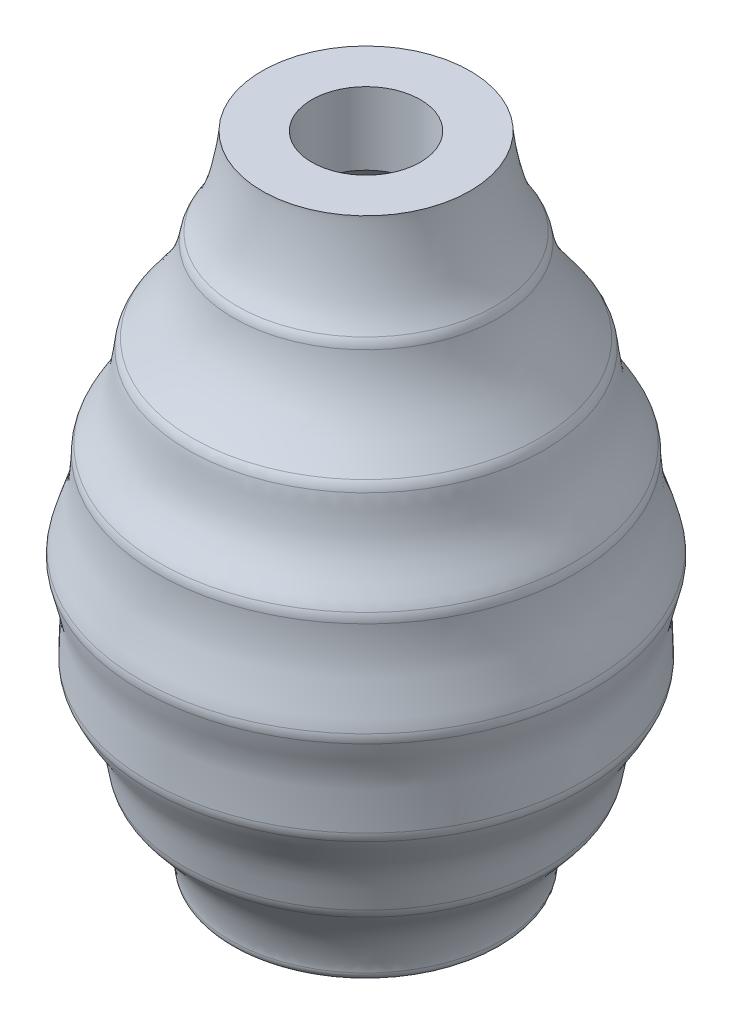
SolidWorks part; units mm, degrees
ref_plane "Front Plane" through (0, 0, 0) normal (0, 0, 1) x (1, 0, 0)
ref_plane "Top Plane" through (0, 0, 0) normal (0, 1, 0) x (1, 0, 0)
ref_plane "Right Plane" through (0, 0, 0) normal (1, 0, 0) x (0, 0, -1)
sketch "Sketch1" plane through (0, 0, 0) normal (0, 0, 1) x (1, 0, 0)
  line L0 (0, 0) -> (0, 16.1018)
  line L1 (0, 16.1018) -> (0, 32.2036)
  line L2 (0, 32.2036) -> (0, 48.3054)
  line L3 (0, 48.3054) -> (0, 64.4071)
  line L4 (0, 64.4071) -> (0, 80.5089)
  line L5 (0, 80.5089) -> (0, 96.6107)
  line L6 (0, 96.6107) -> (0, 112.7125)
  line L7 (0, 112.7125) -> (18.2562, 112.7125)
  line L8 (18.2562, 112.7125) -> (23.0187, 96.6107) construction
  line L9 (23.0187, 96.6107) -> (30.9563, 80.5089) construction
  line L10 (30.9563, 80.5089) -> (36.5125, 64.4071) construction
  line L11 (36.5125, 64.4071) -> (39.6875, 48.3054) construction
  line L12 (39.6875, 48.3054) -> (38.1, 32.2036) construction
  line L13 (38.1, 32.2036) -> (31.75, 16.1018) construction
  line L14 (31.75, 16.1018) -> (22.225, 0) construction
  line L15 (22.225, 0) -> (0, 0)
  line L16 (0, 96.6107) -> (23.0187, 96.6107) construction
  line L17 (0, 80.5089) -> (30.9563, 80.5089) construction
  line L18 (0, 64.4071) -> (36.5125, 64.4071) construction
  line L19 (0, 48.3054) -> (39.6875, 48.3054) construction
  line L20 (0, 32.2036) -> (38.1, 32.2036) construction
  line L21 (0, 16.1018) -> (31.75, 16.1018) construction
  line L22 (18.2562, 112.7125) -> (18.2563, 118.6616) construction
  line L23 (23.2087, 95.8487) -> (23.3634, 94.8513) construction
  arc A0 (22.6174, 97.3727) -> (23.2087, 95.8487) centre (19.4437, 95.2648) cw
  arc A1 (30.4914, 81.2709) -> (31.1875, 79.7469) centre (27.4587, 78.9647) cw
  arc A2 (36.2772, 65.1691) -> (36.5844, 63.6451) centre (32.7745, 63.6701) cw
  arc A3 (39.6062, 49.0674) -> (39.6149, 47.5434) centre (35.8776, 48.284) cw
  arc A4 (38.1686, 32.9656) -> (37.8684, 31.4416) centre (34.3588, 32.9243) cw
  arc A5 (31.972, 16.8638) -> (31.3316, 15.3398) centre (28.2229, 17.5426) cw
  arc A6 (23.749, 1.524) -> (22.225, 0) centre (22.225, 1.524) cw
  spline S0 degree 3 poles (18.2562, 112.7125) (18.2562, 111.6644) (19.3415, 102.408) (22.2739, 97.8899) (22.6174, 97.3727) knots 0 0 0 0 0.872613 1 1 1 1
  spline S1 degree 3 poles (23.2087, 95.8487) (23.6406, 93.0641) (25.3854, 88.0063) (28.5023, 83.8865) (30.4914, 81.2709) knots 0 0 0 0 0.465363 1 1 1 1
  spline S2 degree 3 poles (31.1875, 79.7469) (31.4882, 78.3134) (31.6306, 71.6958) (35.5913, 66.7718) (36.2772, 65.1691) knots 0 0 0 0 0.45435 1 1 1 1
  spline S3 degree 3 poles (36.5844, 63.6451) (36.5726, 61.8388) (36.8918, 55.9925) (39.0473, 51.7273) (39.6062, 49.0674) knots 0 0 0 0 0.460302 1 1 1 1
  spline S4 degree 3 poles (39.6149, 47.5434) (39.2048, 45.4739) (37.3965, 40.761) (38.1352, 36.051) (38.1686, 32.9656) knots 0 0 0 0 0.421679 1 1 1 1
  spline S5 degree 3 poles (37.8684, 31.4416) (36.693, 28.6595) (33.2404, 24.9013) (32.4258, 19.3704) (31.972, 16.8638) knots 0 0 0 0 0.517161 1 1 1 1
  spline S6 degree 3 poles (31.3316, 15.3398) (29.6443, 12.9586) (25.3993, 9.8481) (23.749, 2.4761) (23.749, 1.524) knots 0 0 0 0 0.647991 1 1 1 1
  dimension "D16" = 3.81
  dimension "D20" = 3.81
  dimension "D26" = 3.81
  dimension "D31" = 3.81
  dimension "D37" = 3.81
  dimension "D43" = 3.81
  dimension "D1" = 112.7125
  dimension "D2" = 18.2562
  dimension "D3" = 23.0188
  dimension "D4" = 30.9562
  dimension "D5" = 36.5125
  dimension "D6" = 39.6875
  dimension "D7" = 38.1
  dimension "D8" = 31.75
  dimension "D9" = 22.225
  dimension "D10" = 5.9491
  dimension "D11" = 13.5946
  dimension "D12" = 3.3005
  dimension "D13" = 0.762
  dimension "D14" = 0.4013
  dimension "D15" = 0.762
  dimension "D17" = 0.762
  dimension "D18" = 0.762
  dimension "D19" = 0.9974
  dimension "D21" = 7.2889
  dimension "D22" = 2.353
  dimension "D23" = 0.4649
  dimension "D24" = 0.762
  dimension "D25" = 0.762
  dimension "D27" = 7.0973
  dimension "D28" = 1.2183
  dimension "D29" = 0.762
  dimension "D30" = 0.762
  dimension "D32" = 6.8535
  dimension "D33" = 0.6711
  dimension "D34" = 0.0813
  dimension "D35" = 0.762
  dimension "D36" = 0.762
  dimension "D38" = 6.0436
  dimension "D39" = 1.4823
  dimension "D40" = 0.7651
  dimension "D41" = 0.762
  dimension "D42" = 0.762
  dimension "D44" = 7.1434
  dimension "D45" = 4.0409
  dimension "D46" = 0.222
  dimension "D47" = 1.524
  dimension "D48" = 8.2017
  dimension "D49" = 6.0993
  dimension "D50" = 1.524
revolve "Revolve1" add sketch "Sketch1" angle 360 about L4
sketch "Sketch3" plane through (0, 0, 0) normal (0, 0, 1) x (1, 0, 0)
  line L0 (0, 112.7125) -> (9.525, 112.7125)
  line L1 (0, 112.7125) -> (18.2562, 112.7125) construction
  line L2 (9.525, 112.7125) -> (9.525, 100.0125)
  line L3 (17.78, 6.35) -> (0, 6.35)
  line L4 (0, 0) -> (0, 16.1018) construction
  line L5 (0, 112.7125) -> (0, 6.35)
  line L6 (22.225, 0) -> (0, 0) construction
  spline S0 degree 2 poles (9.525, 100.0125) (48.0926, 54.909) (17.78, 6.35) knots 0 0 0 1 1 1
  dimension "D1" = 9.525
  dimension "D2" = 12.7
  dimension "D3" = 6.35
  dimension "D4" = 17.78
  dimension "D5" = 50.8
  dimension "D6" = 21.59
revolve "Cut-Revolve1" cut sketch "Sketch3" angle 360 about L4
